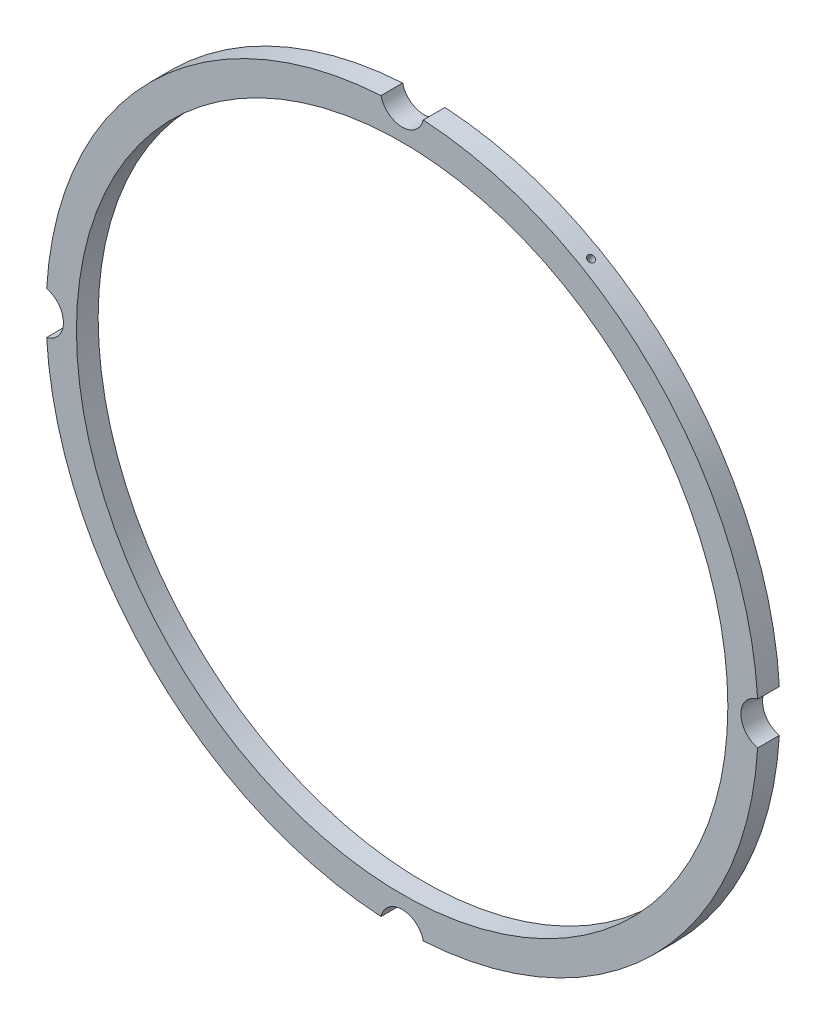
SolidWorks part; units mm, degrees
ref_plane "Front Plane" through (0, 0, 0) normal (0, 0, 1) x (1, 0, 0)
ref_plane "Top Plane" through (0, 0, 0) normal (0, 1, 0) x (1, 0, 0)
ref_plane "Right Plane" through (0, 0, 0) normal (1, 0, 0) x (0, 0, -1)
sketch "Sketch1" plane through (0, 0, 0) normal (0, 0, 1) x (1, 0, 0)
  circle A0 centre (0, 0) radius 75
  circle A1 centre (0, 0) radius 82
extrude "Boss-Extrude1" add sketch "Sketch1" along normal blind 5
sketch "Sketch2" plane through (0, 0, 5) normal (0, 0, 1) x (1, 0, 0)
  circle A0 centre (0, 83) radius 5
extrude "Cut-Extrude1" cut sketch "Sketch2" against normal through all
pattern_circular "CirPattern1" count 4 every 90 about axis through (0, 0, 0) along (0, 0, 1) of "Cut-Extrude1"
hole_wizard "M2x0.4 Tapped Hole1" positions "3DSketch1" profile "Sketch3" tap size "M2x0.4" standard "ANSI Metric"
sketch3d "3DSketch1"
  point P0 (41, 71.0141, 2.5)
cosmetic thread "Hole Thread1" parameters "D1"=4, "D2"=2
sketch "Sketch3" plane through (41, 71.0141, 2.5) normal (0, 0, 1) x (-0.866, 0.5, 0)
  line L0 (0, 0) -> (0, 10.4807)
  line L1 (0, 10.4807) -> (0.8, 10)
  line L2 (0.8, 10) -> (0.8, 0)
  line L5 (0.8, 0) -> (0, 0)
  line L10 (0, 10.4807) -> (-0.8, 10) construction
  line L11 (0, -6.35) -> (0, 107.95) construction
  dimension "Tap Drill Dia." = 1.6
  dimension "Tap Drill Depth" = 10
  dimension "Drill Angle" = 118
